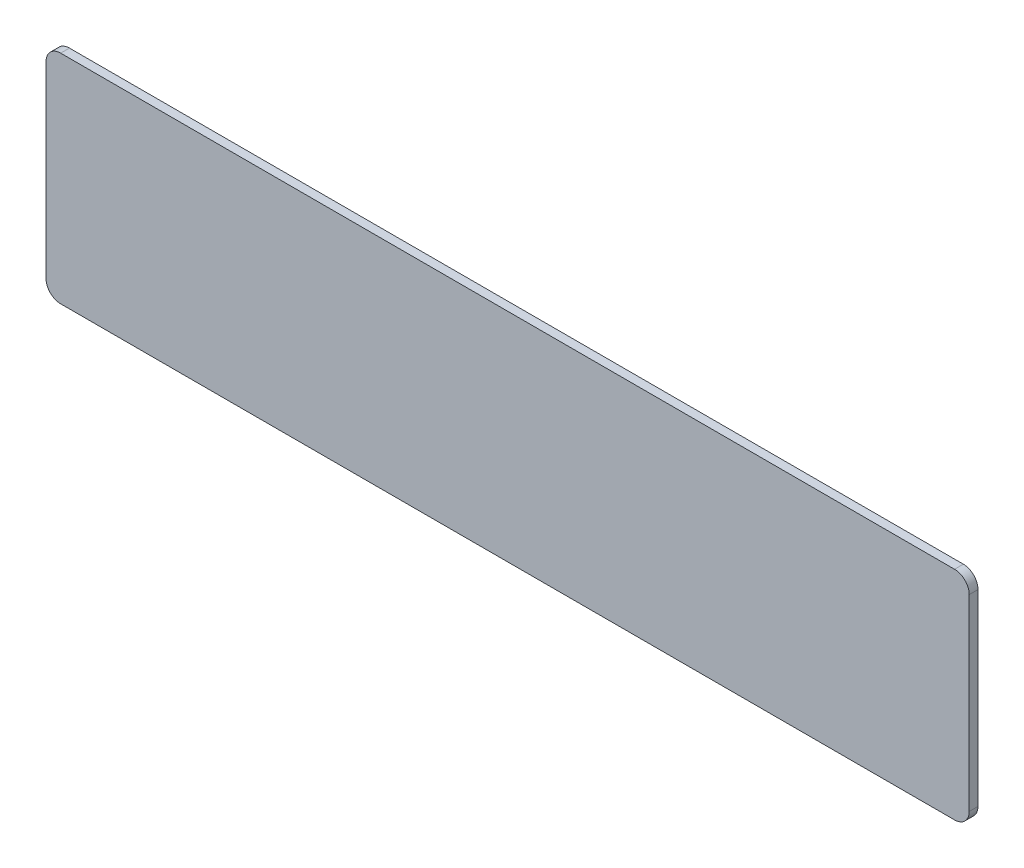
SolidWorks part; units mm, degrees
material "ABS PC"
ref_plane "Front Plane" through (0, 0, 0) normal (0, 0, 1) x (1, 0, 0)
ref_plane "Top Plane" through (0, 0, 0) normal (0, 1, 0) x (1, 0, 0)
ref_plane "Right Plane" through (0, 0, 0) normal (1, 0, 0) x (0, 0, -1)
sketch "草图1" plane through (0, 0, 0) normal (0, 0, 1) x (1, 0, 0)
  line L0 (-152.55, -37.05) -> (152.55, -37.05)
  line L1 (-157.55, 32.05) -> (-157.55, -32.05)
  line L2 (-152.55, 37.05) -> (152.55, 37.05)
  line L3 (157.55, 32.05) -> (157.55, -32.05)
  arc A0 (157.55, 32.05) -> (152.55, 37.05) centre (152.55, 32.05) ccw
  arc A1 (152.55, -37.05) -> (157.55, -32.05) centre (152.55, -32.05) ccw
  arc A2 (-152.55, 37.05) -> (-157.55, 32.05) centre (-152.55, 32.05) ccw
  arc A3 (-157.55, -32.05) -> (-152.55, -37.05) centre (-152.55, -32.05) ccw
extrude "凸台-拉伸1" add sketch "草图1" along normal blind 3 contours L2 A0 L3 A1 L0 A3 L1 A2
